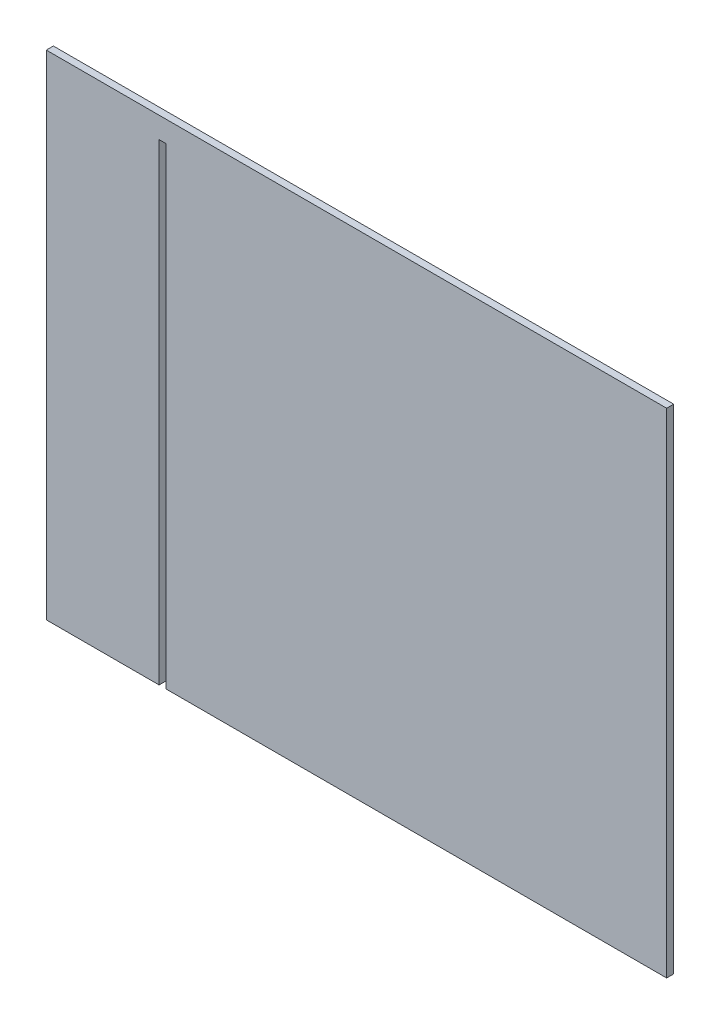
SolidWorks part; units mm, degrees
ref_plane "Alzado" through (0, 0, 0) normal (0, 0, 1) x (1, 0, 0)
ref_plane "Planta" through (0, 0, 0) normal (0, 1, 0) x (1, 0, 0)
ref_plane "Vista lateral" through (0, 0, 0) normal (1, 0, 0) x (0, 0, -1)
sketch "Croquis1" plane through (0, 0, 0) normal (0, 0, 1) x (1, 0, 0)
  line L1 (-165.6686, 115.0145) -> (274.3314, 115.0145)
  line L2 (-165.6686, 115.0145) -> (-165.6686, -234.9855)
  line L3 (-165.6686, -234.9855) -> (274.3314, -234.9855)
  line L4 (274.3314, 115.0145) -> (274.3314, -234.9855)
  dimension "D1" = 440
  dimension "D2" = 350
extrude "Saliente-Extruir1" add sketch "Croquis1" along normal blind 5
sketch "Croquis2" plane through (0, 0, 5) normal (0, 0, 1) x (1, 0, 0)
  line L0 (-165.6686, -234.9855) -> (274.3314, -234.9855) construction
  line L1 (-85.6686, -234.9855) -> (-80.6686, -234.9855)
  line L2 (-85.6686, -234.9855) -> (-85.6686, 100.0145)
  line L3 (-85.6686, 100.0145) -> (-80.6686, 100.0145)
  line L4 (-80.6686, -234.9855) -> (-80.6686, 100.0145)
  line L5 (-165.6686, 115.0145) -> (-165.6686, -234.9855) construction
  line L6 (274.3314, 115.0145) -> (-165.6686, 115.0145) construction
  dimension "D1" = 5
  dimension "D2" = 80
  dimension "D3" = 15
extrude "Cortar-Extruir1" cut sketch "Croquis2" against normal blind 5
